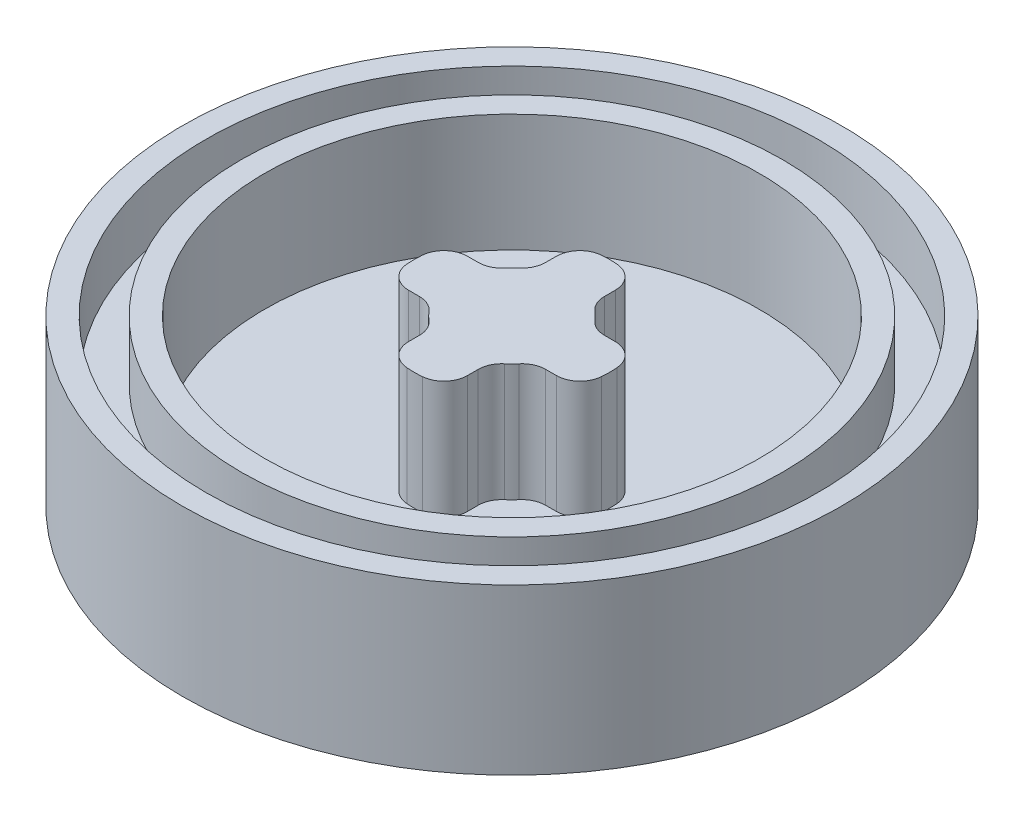
SolidWorks part; units mm, degrees
ref_plane "Front Plane" through (0, 0, 0) normal (0, 0, 1) x (1, 0, 0)
ref_plane "Top Plane" through (0, 0, 0) normal (0, 1, 0) x (1, 0, 0)
ref_plane "Right Plane" through (0, 0, 0) normal (1, 0, 0) x (0, 0, -1)
sketch "Sketch1" plane through (0, 0, 0) normal (0, 0, 1) x (1, 0, 0)
  line L0 (0, 0) -> (-28, 0)
  line L1 (-28, 0) -> (-28, 14)
  line L2 (-28, 14) -> (-26, 14)
  line L3 (-26, 14) -> (-26, 9)
  line L4 (-26, 9) -> (-23, 9)
  line L5 (-23, 9) -> (-23, 14)
  line L6 (-23, 14) -> (-21, 14)
  line L7 (-21, 14) -> (-21, 4)
  line L8 (-21, 4) -> (0, 4)
  line L11 (0, 4) -> (0, 0)
  point P10 (0, 0)
  dimension "D1" = 21
  dimension "D2" = 10
  dimension "D6" = 4
  dimension "D7" = 2
  dimension "D8" = 2
  dimension "D9" = 3
  dimension "D10" = 5
revolve "Revolve1" add sketch "Sketch1" angle 360 about L11
sketch "Sketch3" plane through (0, 4, 0) normal (0, 1, 0) x (1, 0, 0)
  line L0 (2.5, 6.2801) -> (2.5, 5.3619)
  line L1 (0, 0) -> (0, 8.3) construction
  line L2 (0, 0) -> (3.5355, 3.5355) construction
  line L3 (-2.5, 6.2801) -> (-2.5, 5.3619)
  line L4 (6.2801, -2.5) -> (5.3619, -2.5)
  line L5 (6.2801, 2.5) -> (5.3619, 2.5)
  line L6 (-2.5, -6.2801) -> (-2.5, -5.3619)
  line L7 (2.5, -6.2801) -> (2.5, -5.3619)
  line L8 (-6.2801, 2.5) -> (-5.3619, 2.5)
  line L9 (-6.2801, -2.5) -> (-5.3619, -2.5)
  arc A0 (-0.6587, 8.2738) -> (0.6587, 8.2738) centre (0, 0) cw
  arc A1 (3.2143, 3.8299) -> (3.5355, 3.5355) centre (0, 0) cw
  arc A2 (0.6587, 8.2738) -> (2.5, 6.2801) centre (0.5, 6.2801) cw
  arc A3 (3.2143, 3.8299) -> (2.5, 5.3619) centre (4.5, 5.3619) cw
  arc A4 (-3.2143, 3.8299) -> (-2.5, 5.3619) centre (-4.5, 5.3619) ccw
  arc A5 (-0.6587, 8.2738) -> (-2.5, 6.2801) centre (-0.5, 6.2801) ccw
  arc A6 (-3.2143, 3.8299) -> (-3.5355, 3.5355) centre (0, 0) ccw
  arc A7 (3.8299, -3.2143) -> (3.5355, -3.5355) centre (0, 0) cw
  arc A8 (3.8299, -3.2143) -> (5.3619, -2.5) centre (5.3619, -4.5) cw
  arc A9 (8.2738, -0.6587) -> (6.2801, -2.5) centre (6.2801, -0.5) cw
  arc A10 (8.2738, 0.6587) -> (8.2738, -0.6587) centre (0, 0) cw
  arc A11 (8.2738, 0.6587) -> (6.2801, 2.5) centre (6.2801, 0.5) ccw
  arc A12 (3.8299, 3.2143) -> (5.3619, 2.5) centre (5.3619, 4.5) ccw
  arc A13 (3.8299, 3.2143) -> (3.5355, 3.5355) centre (0, 0) ccw
  arc A14 (-3.2143, -3.8299) -> (-3.5355, -3.5355) centre (0, 0) cw
  arc A15 (-3.2143, -3.8299) -> (-2.5, -5.3619) centre (-4.5, -5.3619) cw
  arc A16 (-0.6587, -8.2738) -> (-2.5, -6.2801) centre (-0.5, -6.2801) cw
  arc A17 (0.6587, -8.2738) -> (-0.6587, -8.2738) centre (0, 0) cw
  arc A18 (0.6587, -8.2738) -> (2.5, -6.2801) centre (0.5, -6.2801) ccw
  arc A19 (3.2143, -3.8299) -> (2.5, -5.3619) centre (4.5, -5.3619) ccw
  arc A20 (3.2143, -3.8299) -> (3.5355, -3.5355) centre (0, 0) ccw
  arc A21 (-3.8299, 3.2143) -> (-3.5355, 3.5355) centre (0, 0) cw
  arc A22 (-3.8299, 3.2143) -> (-5.3619, 2.5) centre (-5.3619, 4.5) cw
  arc A23 (-8.2738, 0.6587) -> (-6.2801, 2.5) centre (-6.2801, 0.5) cw
  arc A24 (-8.2738, -0.6587) -> (-8.2738, 0.6587) centre (0, 0) cw
  arc A25 (-8.2738, -0.6587) -> (-6.2801, -2.5) centre (-6.2801, -0.5) ccw
  arc A26 (-3.8299, -3.2143) -> (-5.3619, -2.5) centre (-5.3619, -4.5) ccw
  arc A27 (-3.8299, -3.2143) -> (-3.5355, -3.5355) centre (0, 0) ccw
  point P62 (0, 0)
  dimension "D1" = 8.3
  dimension "D2" = 5
  dimension "D5" = 2
  dimension "D3" = 5
  dimension "D4" = 45
  dimension "D6" = 4
extrude "Boss-Extrude1" add sketch "Sketch3" along normal blind 10 contours A26 A27 A14 A15 L6 A16 A17 A18 L7 A19 A20 A7 A8 L4 A9 A10 A11 L5 A12 A13 A1 A3 L0 A2 A0 A5 L3 A4 A6 A21 A22 L8 A23 A24 A25 L9
